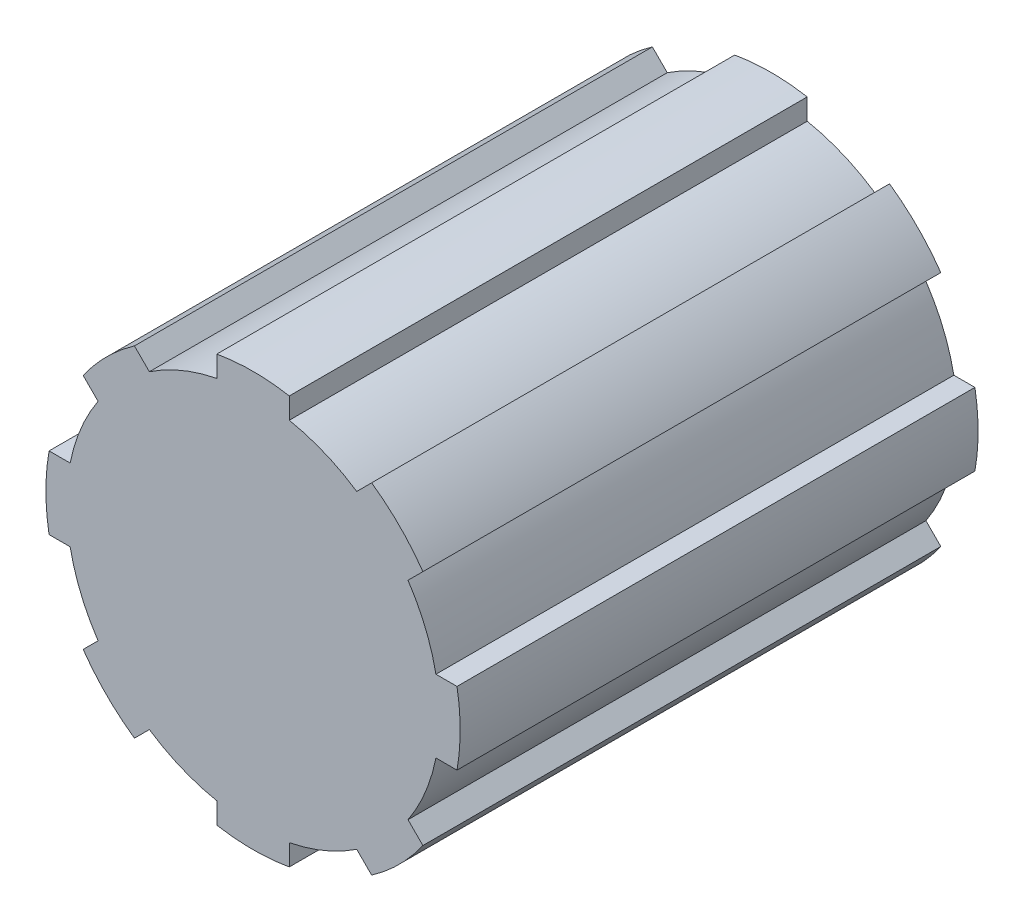
SolidWorks part; units mm, degrees
ref_plane "Front" through (0, 0, 0) normal (0, 0, 1) x (1, 0, 0)
ref_plane "Top" through (0, 0, 0) normal (0, 1, 0) x (1, 0, 0)
ref_plane "Right" through (0, 0, 0) normal (1, 0, 0) x (0, 0, -1)
sketch "Sketch1" plane through (0, 0, 0) normal (0, 0, 1) x (1, 0, 0)
  circle A0 centre (0, 0) radius 18
  dimension "d" = 36
extrude "BaseKey" add sketch "Sketch1" along normal mid plane 50
sketch "Sketch2" plane through (0, 0, 0) normal (0, 0, 1) x (1, 0, 0)
  line L0 (0, 9.5196) -> (0, -9.8317) construction
  line L1 (-3.5, 19.6914) -> (-3.5, 0)
  line L2 (-3.5, 0) -> (3.5, 0)
  line L3 (3.5, 0) -> (3.5, 19.6914)
  arc A0 (3.5, 19.6914) -> (-3.5, 19.6914) centre (0, 0) ccw
  dimension "D" = 40
  dimension "B" = 7
  dimension "B1" = 3.5
extrude "Rectangle" add sketch "Sketch2" along normal mid plane 50
pattern_circular "RectanglePat" count 8 over 360 about axis through (0, 0, 0) along (0, 0, 1) of "Rectangle"
sketch "草图1" plane through (0, 0, -25) normal (0, 0, -1) x (-1, 0, 0)
  circle A0 centre (0, 0) radius 10
extrude "切除-拉伸1" cut sketch "草图1" against normal blind 22
sketch "草图3" plane through (0, 0, 0) normal (0, 1, 0) x (1, 0, 0)
  line L0 (0, 37.1543) -> (0, -34.0775) construction
  line L1 (5, 25) -> (-5, 25)
  line L2 (3.5, 25) -> (-3.5, 25) construction
  line L3 (-3.5, 25) -> (-10.0101, 25) construction
  line L4 (-5, 18) -> (-5, 25)
  line L5 (-5, 18) -> (-5, 3)
  line L6 (5, 25) -> (5, 18)
  line L7 (-5, 3) -> (5, 3)
  line L8 (5, 3) -> (5, 18)
  point P12 (0, 13)
  point P13 (0, 25)
  dimension "D1" = 22
extrude "切除-拉伸2" cut sketch "草图3" along normal blind 14
equation "\"B1@Sketch2\" = \"B@Sketch2\" / 2"
equation "\"L1@Rectangle\" = \"L@BaseKey\""
